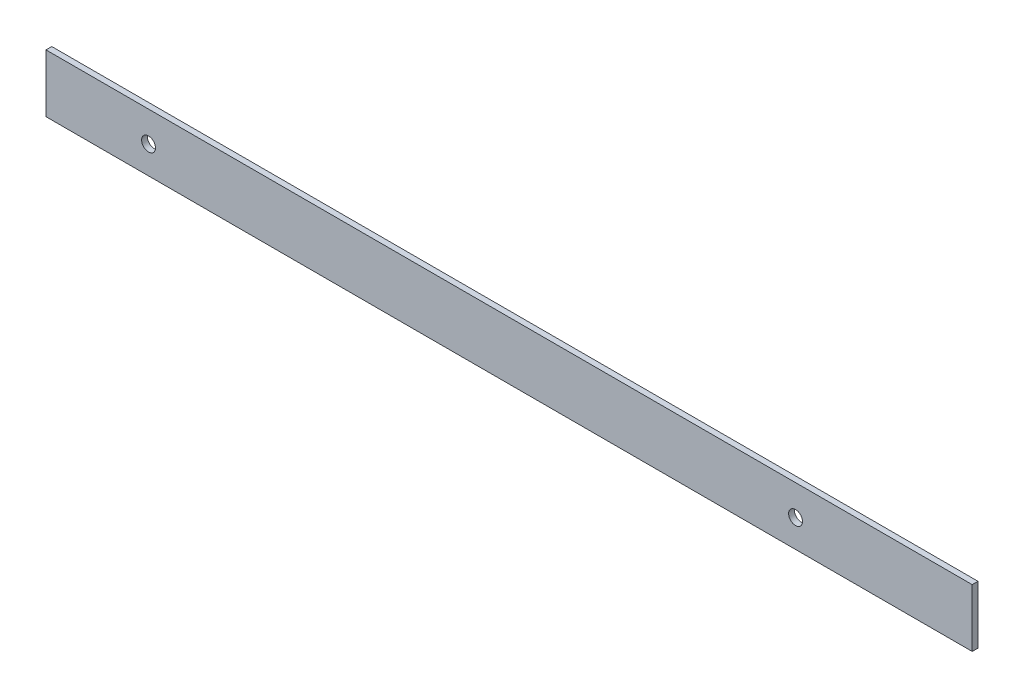
SolidWorks part; units mm, degrees
ref_plane "Płaszczyzna przednia" through (0, 0, 0) normal (0, 0, 1) x (1, 0, 0)
ref_plane "Płaszczyzna górna" through (0, 0, 0) normal (0, 1, 0) x (1, 0, 0)
ref_plane "Płaszczyzna prawa" through (0, 0, 0) normal (1, 0, 0) x (0, 0, -1)
sketch "Szkic1" plane through (0, 0, 0) normal (0, 0, 1) x (1, 0, 0)
  line L0 (400, 0) -> (400, 50)
  line L1 (0, 0) -> (800, 0)
  line L2 (0, 0) -> (0, 50)
  line L3 (0, 50) -> (800, 50)
  line L4 (800, 0) -> (800, 50)
  circle A0 centre (88.5629, 23.8811) radius 6
  circle A1 centre (647.4122, 23.8811) radius 6
  dimension "D5" = 12
  dimension "D6" = 12
  dimension "D1" = 800
  dimension "D2" = 50
extrude "Dodanie-wyciągnięcie1" add sketch "Szkic1" along normal blind 5 contours L3 L2 L1 L0 A0 | L1 L4 L3 L0 A1
